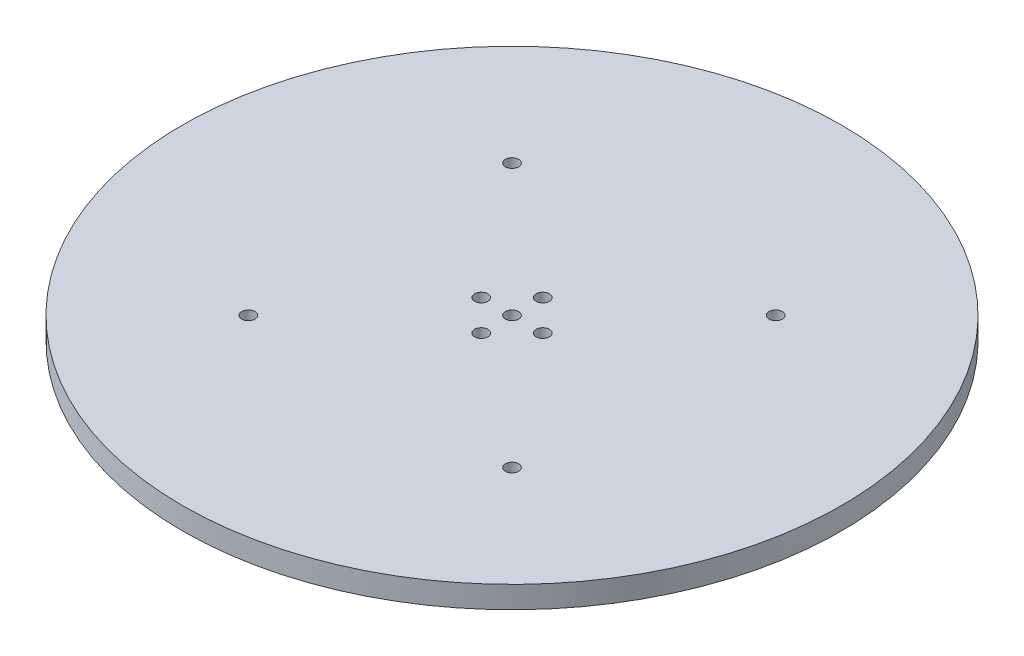
SolidWorks part; units mm, degrees
ref_plane "Alzado" through (0, 0, 0) normal (0, 0, 1) x (1, 0, 0)
ref_plane "Planta" through (0, 0, 0) normal (0, 1, 0) x (1, 0, 0)
ref_plane "Vista lateral" through (0, 0, 0) normal (1, 0, 0) x (0, 0, -1)
sketch "Croquis1" plane through (0, 0, 0) normal (0, 1, 0) x (1, 0, 0)
  circle A0 centre (0, 0) radius 75
  dimension "D1" = 150
extrude "Saliente-Extruir1" add sketch "Croquis1" along normal blind 5
sketch "Croquis2" plane through (0, 5, 0) normal (0, 1, 0) x (1, 0, 0)
  line L0 (0, 0) -> (7, 0)
  line L1 (7, 0) -> (-7, 0)
  line L2 (0, 0) -> (0, -7)
  line L3 (0, -7) -> (0, 7)
  circle A0 centre (0, 0) radius 1.5
  circle A1 centre (0, 7) radius 1.5
  circle A2 centre (7, 0) radius 1.5
  circle A3 centre (0, -7) radius 1.5
  circle A4 centre (-7, 0) radius 1.5
  dimension "D1" = 3
  dimension "D6" = 3
  dimension "D7" = 3
  dimension "D8" = 3
  dimension "D9" = 3
  dimension "D2" = 7
  dimension "D3" = 7
  dimension "D4" = 7
  dimension "D5" = 7
extrude "Cortar-Extruir1" cut sketch "Croquis2" against normal blind 5
sketch "Croquis3" plane through (0, 5, 0) normal (0, 1, 0) x (1, 0, 0)
  line L1 (-30, -30) -> (30, -30)
  line L2 (-30, -30) -> (-30, 30)
  line L3 (-30, 30) -> (30, 30)
  line L4 (30, -30) -> (30, 30)
  line L5 (-30, -30) -> (30, 30) construction
  line L6 (-30, 30) -> (30, -30) construction
  circle A0 centre (-30, 30) radius 1.5
  circle A1 centre (30, 30) radius 1.5
  circle A2 centre (30, -30) radius 1.5
  circle A3 centre (-30, -30) radius 1.5
  point P0 (0, 0)
  dimension "D3" = 3
  dimension "D4" = 3
  dimension "D5" = 3
  dimension "D6" = 3
  dimension "D1" = 60
  dimension "D2" = 60
extrude "Cortar-Extruir2" cut sketch "Croquis3" against normal blind 5 contours L4 A1 L3 | L3 A1 L4 | L2 A3 L1 | L1 A3 L2 | L4 A2 L1 | L1 A2 L4 | A0
